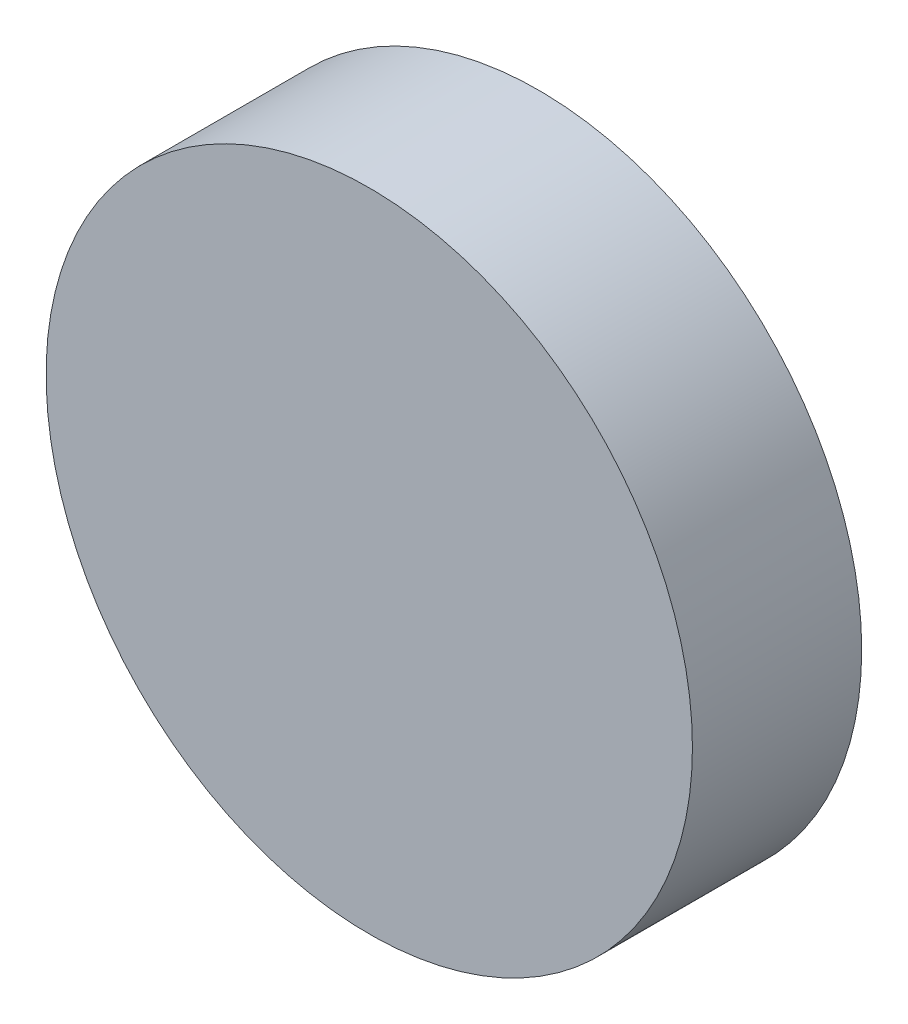
SolidWorks part; units mm, degrees
ref_plane "Front Plane" through (0, 0, 0) normal (0, 0, 1) x (1, 0, 0)
ref_plane "Top Plane" through (0, 0, 0) normal (0, 1, 0) x (1, 0, 0)
ref_plane "Right Plane" through (0, 0, 0) normal (1, 0, 0) x (0, 0, -1)
sketch "Sketch1" plane through (0, 0, 0) normal (0, 0, 1) x (1, 0, 0)
  circle A0 centre (0, 0) radius 210
  dimension "D1" = 420
extrude "Boss-Extrude1" add sketch "Sketch1" along normal blind 110
